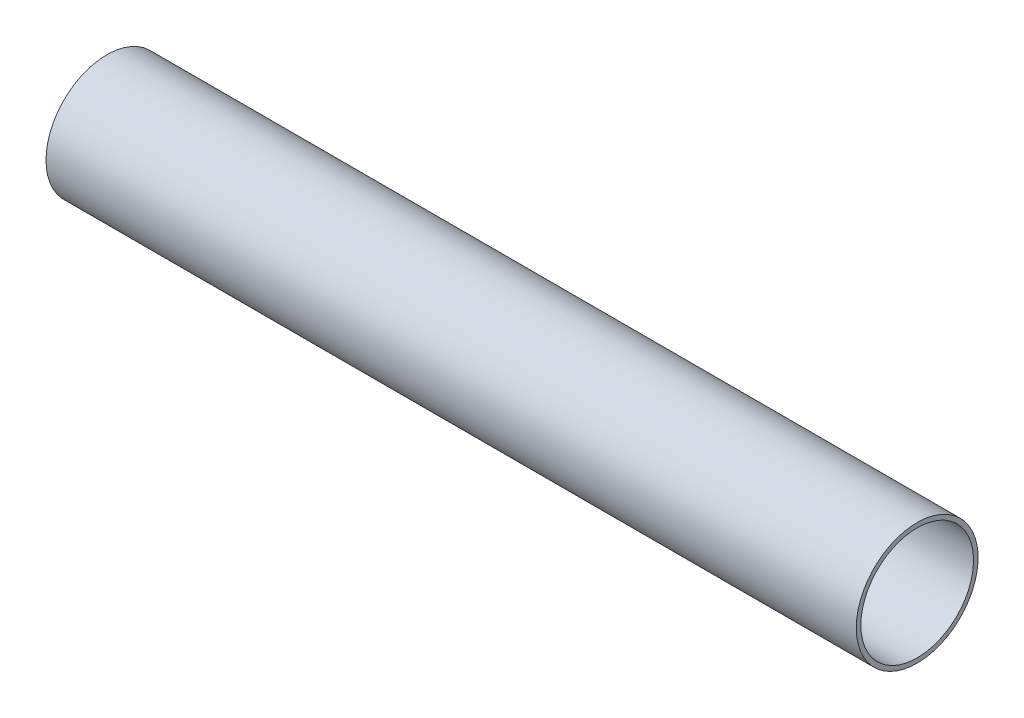
SolidWorks part; units mm, degrees
material "Silicon Rubber"
ref_plane "Front Plane" through (0, 0, 0) normal (0, 0, 1) x (1, 0, 0)
ref_plane "Top Plane" through (0, 0, 0) normal (0, 1, 0) x (1, 0, 0)
ref_plane "Right Plane" through (0, 0, 0) normal (1, 0, 0) x (0, 0, -1)
sketch "Sketch1" plane through (0, 0, 0) normal (1, 0, 0) x (0, 0, -1)
  circle A0 centre (0, 0) radius 15.875
  circle A1 centre (0, 0) radius 17.1714
  dimension "D1" = 34.3429
  dimension "D2" = 31.75
extrude "Boss-Extrude1" add sketch "Sketch1" along normal mid plane 228.346
equation "\"D1@Sketch1\"=sqr((1.25)^2+(1.125)^2-1)"
